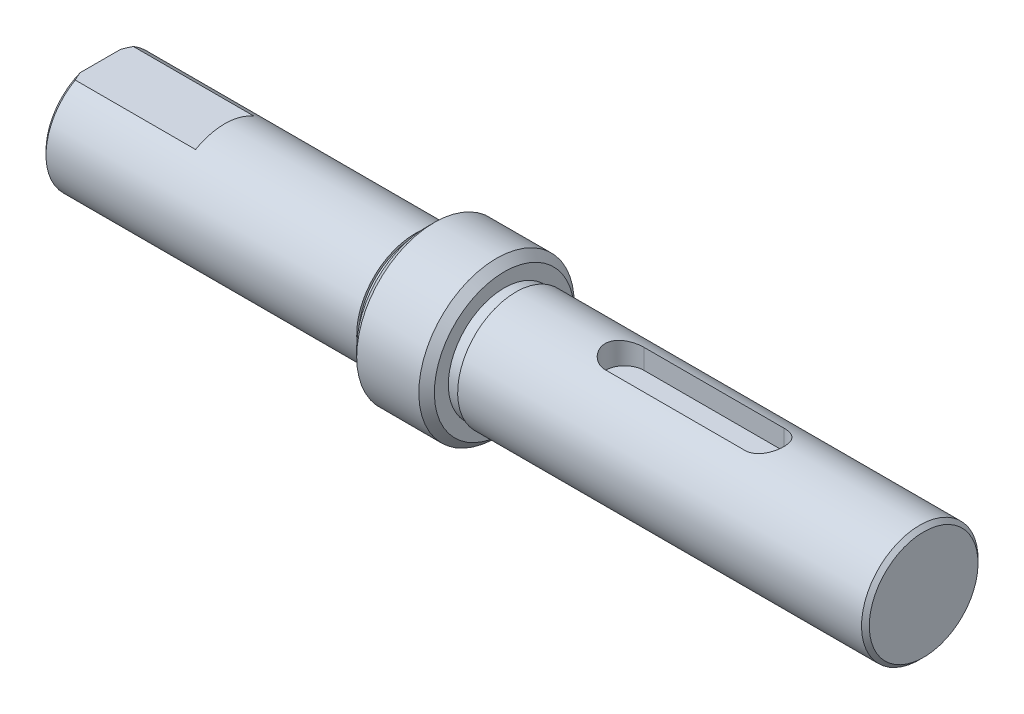
SolidWorks part; units mm, degrees
material "1.4301 (X5CrNi18-10)"
ref_plane "正面" through (0, 0, 0) normal (0, 0, 1) x (1, 0, 0)
ref_plane "平面" through (0, 0, 0) normal (0, 1, 0) x (1, 0, 0)
ref_plane "右側面" through (0, 0, 0) normal (1, 0, 0) x (0, 0, -1)
sketch "ｽｹｯﾁ5" plane through (0, 0, 0) normal (0, 0, 1) x (1, 0, 0)
  line L0 (0, 0) -> (0, 7.5)
  line L1 (0, 7.5) -> (40.5, 7.5)
  line L2 (40.5, 7.5) -> (40.5, 7.2)
  line L3 (40.5, 7.2) -> (42, 7.2)
  line L4 (42, 7.2) -> (42, 10)
  line L5 (42, 10) -> (52, 10)
  line L6 (52, 10) -> (52, 7.2)
  line L7 (52, 7.2) -> (53.5, 7.2)
  line L8 (53.5, 7.2) -> (53.5, 7.5)
  line L9 (53.5, 7.5) -> (106, 7.5)
  line L10 (106, 7.5) -> (106, 0)
  line L11 (106, 0) -> (0, 0)
  line L13 (0, 0) -> (-50000, 0) construction
  dimension "D1" = 106
  dimension "D2" = 1.5
  dimension "D3" = 42
  dimension "D4" = 54
  dimension "D5" = 0.3
  dimension "D6" = 15
  dimension "D7" = 20
revolve "回転1" add sketch "ｽｹｯﾁ5" angle 360 about L13
sketch "ｽｹｯﾁ3" plane through (0, 0, 0) normal (0, 0, 1) x (1, 0, 0)
  line L0 (0, 0) -> (-50000, 0) construction
  line L1 (16, 6.5) -> (0, 6.5)
  line L2 (16, 6.5) -> (16, 10)
  line L3 (16, 10) -> (0, 10)
  line L4 (0, 6.5) -> (0, 10)
  line L5 (0, -6.5) -> (16, -6.5)
  line L6 (0, -6.5) -> (0, -10)
  line L7 (0, -10) -> (16, -10)
  line L8 (16, -6.5) -> (16, -10)
  dimension "D1" = 13
  dimension "D2" = 20
  dimension "D3" = 16
extrude "ｶｯﾄ - 押し出し1" cut sketch "ｽｹｯﾁ3" against normal through all both and the other way through all
sketch "ｽｹｯﾁ4" plane through (0, 0, 0) normal (0, 1, 0) x (1, 0, 0)
  line L0 (67.5, 0) -> (85.5, 0) construction
  line L1 (200000, 0) -> (-250000, 0) construction
  line L2 (67.5, 2.5) -> (85.5, 2.5)
  line L3 (67.5, -2.5) -> (85.5, -2.5)
  line L4 (106, -7.5) -> (106, 7.5) construction
  arc A0 (67.5, 2.5) -> (67.5, -2.5) centre (67.5, 0) ccw
  arc A1 (85.5, -2.5) -> (85.5, 2.5) centre (85.5, 0) ccw
  point P4 (76.5, 0)
  dimension "D2" = 18
  dimension "D3" = 23
  dimension "D1" = 5
extrude "ｶｯﾄ - 押し出し2" cut sketch "ｽｹｯﾁ4" along normal through all from offset 4.5
hole_wizard "M5x0.8 ねじ穴1" positions "3Dｽｹｯﾁ1" profile "ｽｹｯﾁ7" tap size "M5x0.8" standard "JIS"
sketch3d "3Dｽｹｯﾁ1"
  point P0 (0, 0, 0)
sketch "ｽｹｯﾁ7" plane through (0, 0, 0) normal (0, 1, 0) x (0, 0, 1)
  line L0 (0, 0) -> (0, 15.2618)
  line L1 (0, 15.2618) -> (2.1, 14)
  line L2 (2.1, 14) -> (2.1, 10)
  line L3 (2.1, 10) -> (2.5, 10)
  line L4 (2.5, 10) -> (2.5, 0)
  line L5 (2.5, 0) -> (0, 0)
  line L10 (0, 15.2618) -> (-2.1, 14) construction
  line L11 (0, -6.35) -> (0, 107.95) construction
  dimension "ねじ下穴ﾄﾞﾘﾙ直径" = 4.2
  dimension "ねじ下穴ﾄﾞﾘﾙの深さ" = 14
  dimension "ねじ山の主要直径" = 5
  dimension "ねじ山の深さ" = 10
  dimension "ﾄﾞﾘﾙ角度" = 118
chamfer "面取り1" distance 1 angle 45 2 edges at (52, 10, 0) (42, 10, 0)
chamfer "面取り2" distance 0.5 angle 45 3 edges at (106, 7.5, 0) (0, 0, -7.5) (0, 0, 7.5)
